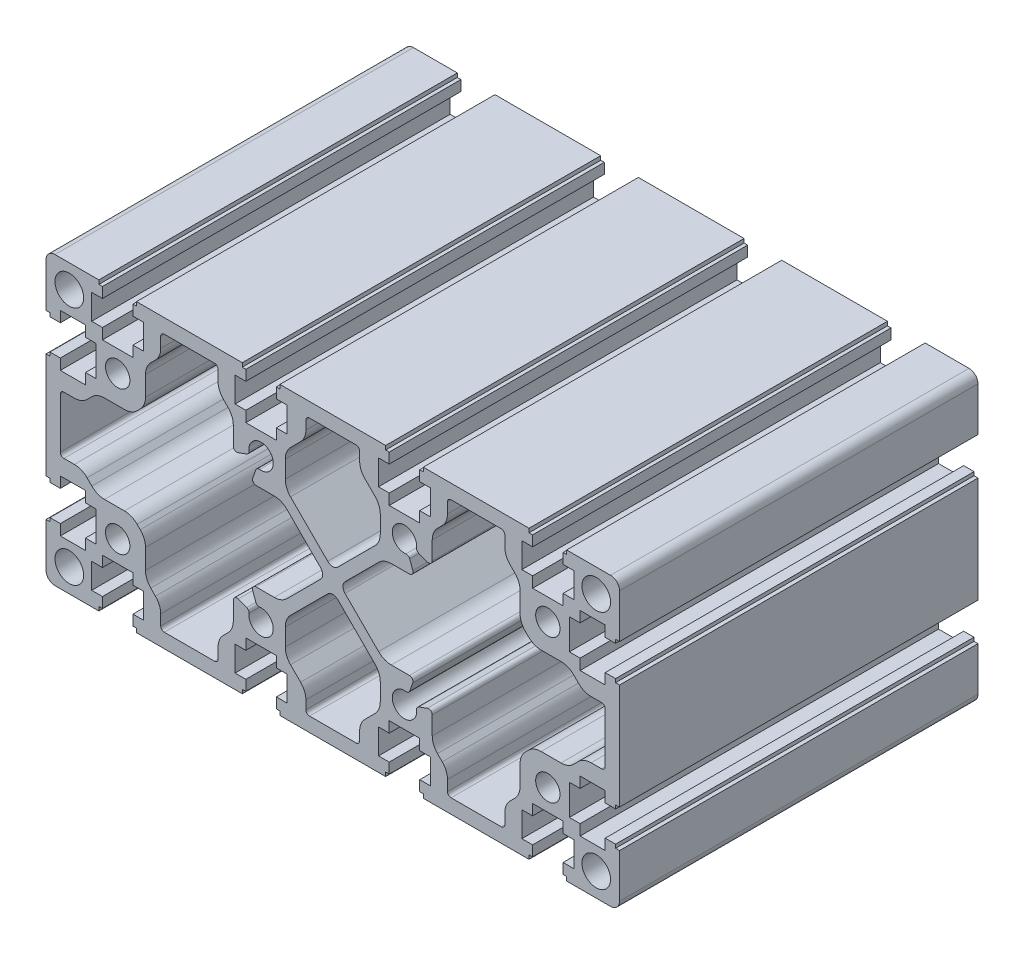
SolidWorks part; units mm, degrees
ref_plane "前视基准面" through (0, 0, 0) normal (0, 0, 1) x (1, 0, 0)
ref_plane "上视基准面" through (0, 0, 0) normal (0, 1, 0) x (1, 0, 0)
ref_plane "右视基准面" through (0, 0, 0) normal (1, 0, 0) x (0, 0, -1)
sketch "草图1" plane through (0, 0, 0) normal (0, 0, 1) x (1, 0, 0)
  line B0 (37.6677, 33.592) -> (38.5345, 35.9736)
  line B1 (35.9736, 38.5345) -> (33.592, 37.6677)
  line B2 (32.25, 38.6074) -> (32.25, 43.6789)
  line B3 (30.7855, 47.2145) -> (29.4645, 48.5355)
  line B4 (28, 52.0711) -> (28, 55)
  line B5 (27, 56) -> (13, 56)
  line B6 (12, 55) -> (12, 52.0711)
  line B7 (10.5355, 48.5355) -> (9.2145, 47.2145)
  line B8 (7.75, 43.6789) -> (7.75, 38.1211)
  line B9 (6.2855, 34.5855) -> (5.4145, 33.7145)
  line B10 (1.8789, 32.25) -> (-3.6789, 32.25)
  line B11 (-7.2145, 30.7855) -> (-8.5355, 29.4645)
  line B12 (-12.0711, 28) -> (-15, 28)
  line B13 (-16, 27) -> (-16, 13)
  line B14 (-15, 12) -> (-12.0711, 12)
  line B15 (-8.5355, 10.5355) -> (-7.2145, 9.2145)
  line B16 (-3.6789, 7.75) -> (1.8789, 7.75)
  line B17 (5.4145, 6.2855) -> (6.2855, 5.4145)
  line B18 (7.75, 1.8789) -> (7.75, -3.6789)
  line B19 (9.2145, -7.2145) -> (10.5355, -8.5355)
  line B20 (12, -12.0711) -> (12, -15)
  line B21 (13, -16) -> (27, -16)
  line B22 (28, -15) -> (28, -12.0711)
  line B23 (29.4645, -8.5355) -> (30.7855, -7.2145)
  line B24 (32.25, -3.6789) -> (32.25, 1.3926)
  line B25 (33.592, 2.3323) -> (35.9736, 1.4655)
  line B26 (38.5345, 4.0264) -> (37.6677, 6.408)
  line B27 (38.6074, 7.75) -> (43.6789, 7.75)
  line B28 (47.2145, 9.2145) -> (56.5858, 18.5858)
  line B29 (56.5858, 21.4142) -> (47.2145, 30.7855)
  line B30 (43.6789, 32.25) -> (38.6074, 32.25)
  line B31 (67.5, -15) -> (67.5, -12.5966)
  line B32 (68.9645, -9.061) -> (71.7855, -6.24)
  line B33 (73.25, -2.7044) -> (73.25, 2.1534)
  line B34 (71.7855, 5.689) -> (61.4142, 16.0603)
  line B35 (58.5858, 16.0603) -> (48.2145, 5.689)
  line B36 (46.75, 2.1534) -> (46.75, -2.7044)
  line B37 (48.2145, -6.24) -> (51.0355, -9.061)
  line B38 (52.5, -12.5966) -> (52.5, -15)
  line B39 (53.5, -16) -> (66.5, -16)
  line B40 (137.5, 60) -> (125.25, 60)
  line B41 (125.25, 60) -> (125.25, 58.9)
  line B42 (125.25, 58.9) -> (124.25, 58.9)
  line B43 (124.25, 58.9) -> (124.25, 56)
  line B44 (124.25, 56) -> (127.25, 56)
  line B45 (127.25, 56) -> (127.25, 49)
  line B46 (127.25, 49) -> (124.25, 49)
  line B47 (124.25, 49) -> (124.25, 46)
  line B48 (124.25, 46) -> (115.75, 46)
  line B49 (115.75, 46) -> (115.75, 49)
  line B50 (115.75, 49) -> (112.75, 49)
  line B51 (112.75, 49) -> (112.75, 56)
  line B52 (112.75, 56) -> (115.75, 56)
  line B53 (115.75, 56) -> (115.75, 58.9)
  line B54 (115.75, 58.9) -> (114.75, 58.9)
  line B55 (114.75, 58.9) -> (114.75, 60)
  line B56 (114.75, 60) -> (85.25, 60)
  line B57 (85.25, 60) -> (85.25, 58.9)
  line B58 (85.25, 58.9) -> (84.25, 58.9)
  line B59 (84.25, 58.9) -> (84.25, 56)
  line B60 (84.25, 56) -> (87.25, 56)
  line B61 (87.25, 56) -> (87.25, 49)
  line B62 (87.25, 49) -> (84.25, 49)
  line B63 (84.25, 49) -> (84.25, 46)
  line B64 (84.25, 46) -> (75.75, 46)
  line B65 (75.75, 46) -> (75.75, 49)
  line B66 (75.75, 49) -> (72.75, 49)
  line B67 (72.75, 49) -> (72.75, 56)
  line B68 (72.75, 56) -> (75.75, 56)
  line B69 (75.75, 56) -> (75.75, 58.9)
  line B70 (75.75, 58.9) -> (74.75, 58.9)
  line B71 (74.75, 58.9) -> (74.75, 60)
  line B72 (74.75, 60) -> (45.25, 60)
  line B73 (45.25, 60) -> (45.25, 58.9)
  line B74 (45.25, 58.9) -> (44.25, 58.9)
  line B75 (44.25, 58.9) -> (44.25, 56)
  line B76 (44.25, 56) -> (47.25, 56)
  line B77 (47.25, 56) -> (47.25, 49)
  line B78 (47.25, 49) -> (44.25, 49)
  line B79 (44.25, 49) -> (44.25, 46)
  line B80 (44.25, 46) -> (35.75, 46)
  line B81 (35.75, 46) -> (35.75, 49)
  line B82 (35.75, 49) -> (32.75, 49)
  line B83 (32.75, 49) -> (32.75, 56)
  line B84 (32.75, 56) -> (35.75, 56)
  line B85 (35.75, 56) -> (35.75, 58.9)
  line B86 (35.75, 58.9) -> (34.75, 58.9)
  line B87 (34.75, 58.9) -> (34.75, 60)
  line B88 (34.75, 60) -> (5.25, 60)
  line B89 (5.25, 60) -> (5.25, 58.9)
  line B90 (5.25, 58.9) -> (4.25, 58.9)
  line B91 (4.25, 58.9) -> (4.25, 56)
  line B92 (4.25, 56) -> (7.25, 56)
  line B93 (7.25, 56) -> (7.25, 49)
  line B94 (7.25, 49) -> (4.25, 49)
  line B95 (4.25, 49) -> (4.25, 46)
  line B96 (4.25, 46) -> (-4.25, 46)
  line B97 (-4.25, 46) -> (-4.25, 49)
  line B98 (-4.25, 49) -> (-7.25, 49)
  line B99 (-7.25, 49) -> (-7.25, 56)
  line B100 (-7.25, 56) -> (-4.25, 56)
  line B101 (-4.25, 56) -> (-4.25, 58.9)
  line B102 (-4.25, 58.9) -> (-5.25, 58.9)
  line B103 (-5.25, 58.9) -> (-5.25, 60)
  line B104 (-5.25, 60) -> (-17.5, 60)
  line B105 (-20, 57.5) -> (-20, 45.25)
  line B106 (-20, 45.25) -> (-18.9, 45.25)
  line B107 (-18.9, 45.25) -> (-18.9, 44.25)
  line B108 (-18.9, 44.25) -> (-16, 44.25)
  line B109 (-16, 44.25) -> (-16, 47.25)
  line B110 (-16, 47.25) -> (-9, 47.25)
  line B111 (-9, 47.25) -> (-9, 44.25)
  line B112 (-9, 44.25) -> (-6, 44.25)
  line B113 (-6, 44.25) -> (-6, 35.75)
  line B114 (-6, 35.75) -> (-9, 35.75)
  line B115 (-9, 35.75) -> (-9, 32.75)
  line B116 (-9, 32.75) -> (-16, 32.75)
  line B117 (-16, 32.75) -> (-16, 35.75)
  line B118 (-16, 35.75) -> (-18.9, 35.75)
  line B119 (-18.9, 35.75) -> (-18.9, 34.75)
  line B120 (-18.9, 34.75) -> (-20, 34.75)
  line B121 (-20, 34.75) -> (-20, 5.25)
  line B122 (-20, 5.25) -> (-18.9, 5.25)
  line B123 (-18.9, 5.25) -> (-18.9, 4.25)
  line B124 (-18.9, 4.25) -> (-16, 4.25)
  line B125 (-16, 4.25) -> (-16, 7.25)
  line B126 (-16, 7.25) -> (-9, 7.25)
  line B127 (-9, 7.25) -> (-9, 4.25)
  line B128 (-9, 4.25) -> (-6, 4.25)
  line B129 (-6, 4.25) -> (-6, -4.25)
  line B130 (-6, -4.25) -> (-9, -4.25)
  line B131 (-9, -4.25) -> (-9, -7.25)
  line B132 (-9, -7.25) -> (-16, -7.25)
  line B133 (-16, -7.25) -> (-16, -4.25)
  line B134 (-16, -4.25) -> (-18.9, -4.25)
  line B135 (-18.9, -4.25) -> (-18.9, -5.25)
  line B136 (-18.9, -5.25) -> (-20, -5.25)
  line B137 (-20, -5.25) -> (-20, -17.5)
  line B138 (-17.5, -20) -> (-5.25, -20)
  line B139 (-5.25, -20) -> (-5.25, -18.9)
  line B140 (-5.25, -18.9) -> (-4.25, -18.9)
  line B141 (-4.25, -18.9) -> (-4.25, -16)
  line B142 (-4.25, -16) -> (-7.25, -16)
  line B143 (-7.25, -16) -> (-7.25, -9)
  line B144 (-7.25, -9) -> (-4.25, -9)
  line B145 (-4.25, -9) -> (-4.25, -6)
  line B146 (-4.25, -6) -> (4.25, -6)
  line B147 (4.25, -6) -> (4.25, -9)
  line B148 (4.25, -9) -> (7.25, -9)
  line B149 (7.25, -9) -> (7.25, -16)
  line B150 (7.25, -16) -> (4.25, -16)
  line B151 (4.25, -16) -> (4.25, -18.9)
  line B152 (4.25, -18.9) -> (5.25, -18.9)
  line B153 (5.25, -18.9) -> (5.25, -20)
  line B154 (5.25, -20) -> (34.75, -20)
  line B155 (34.75, -20) -> (34.75, -18.9)
  line B156 (34.75, -18.9) -> (35.75, -18.9)
  line B157 (35.75, -18.9) -> (35.75, -16)
  line B158 (35.75, -16) -> (32.75, -16)
  line B159 (32.75, -16) -> (32.75, -9)
  line B160 (32.75, -9) -> (35.75, -9)
  line B161 (35.75, -9) -> (35.75, -6)
  line B162 (35.75, -6) -> (44.25, -6)
  line B163 (44.25, -6) -> (44.25, -9)
  line B164 (44.25, -9) -> (47.25, -9)
  line B165 (47.25, -9) -> (47.25, -16)
  line B166 (47.25, -16) -> (44.25, -16)
  line B167 (44.25, -16) -> (44.25, -18.9)
  line B168 (44.25, -18.9) -> (45.25, -18.9)
  line B169 (45.25, -18.9) -> (45.25, -20)
  line B170 (45.25, -20) -> (74.75, -20)
  line B171 (74.75, -20) -> (74.75, -18.9)
  line B172 (74.75, -18.9) -> (75.75, -18.9)
  line B173 (75.75, -18.9) -> (75.75, -16)
  line B174 (75.75, -16) -> (72.75, -16)
  line B175 (72.75, -16) -> (72.75, -9)
  line B176 (72.75, -9) -> (75.75, -9)
  line B177 (75.75, -9) -> (75.75, -6)
  line B178 (75.75, -6) -> (84.25, -6)
  line B179 (84.25, -6) -> (84.25, -9)
  line B180 (84.25, -9) -> (87.25, -9)
  line B181 (87.25, -9) -> (87.25, -16)
  line B182 (87.25, -16) -> (84.25, -16)
  line B183 (84.25, -16) -> (84.25, -18.9)
  line B184 (84.25, -18.9) -> (85.25, -18.9)
  line B185 (85.25, -18.9) -> (85.25, -20)
  line B186 (85.25, -20) -> (114.75, -20)
  line B187 (114.75, -20) -> (114.75, -18.9)
  line B188 (114.75, -18.9) -> (115.75, -18.9)
  line B189 (115.75, -18.9) -> (115.75, -16)
  line B190 (115.75, -16) -> (112.75, -16)
  line B191 (112.75, -16) -> (112.75, -9)
  line B192 (112.75, -9) -> (115.75, -9)
  line B193 (115.75, -9) -> (115.75, -6)
  line B194 (115.75, -6) -> (124.25, -6)
  line B195 (124.25, -6) -> (124.25, -9)
  line B196 (124.25, -9) -> (127.25, -9)
  line B197 (127.25, -9) -> (127.25, -16)
  line B198 (127.25, -16) -> (124.25, -16)
  line B199 (124.25, -16) -> (124.25, -18.9)
  line B200 (124.25, -18.9) -> (125.25, -18.9)
  line B201 (125.25, -18.9) -> (125.25, -20)
  line B202 (125.25, -20) -> (137.5, -20)
  line B203 (140, -17.5) -> (140, -5.25)
  line B204 (140, -5.25) -> (138.9, -5.25)
  line B205 (138.9, -5.25) -> (138.9, -4.25)
  line B206 (138.9, -4.25) -> (136, -4.25)
  line B207 (136, -4.25) -> (136, -7.25)
  line B208 (136, -7.25) -> (129, -7.25)
  line B209 (129, -7.25) -> (129, -4.25)
  line B210 (129, -4.25) -> (126, -4.25)
  line B211 (126, -4.25) -> (126, 4.25)
  line B212 (126, 4.25) -> (129, 4.25)
  line B213 (129, 4.25) -> (129, 7.25)
  line B214 (129, 7.25) -> (136, 7.25)
  line B215 (136, 7.25) -> (136, 4.25)
  line B216 (136, 4.25) -> (138.9, 4.25)
  line B217 (138.9, 4.25) -> (138.9, 5.25)
  line B218 (138.9, 5.25) -> (140, 5.25)
  line B219 (140, 5.25) -> (140, 34.75)
  line B220 (140, 34.75) -> (138.9, 34.75)
  line B221 (138.9, 34.75) -> (138.9, 35.75)
  line B222 (138.9, 35.75) -> (136, 35.75)
  line B223 (136, 35.75) -> (136, 32.75)
  line B224 (136, 32.75) -> (129, 32.75)
  line B225 (129, 32.75) -> (129, 35.75)
  line B226 (129, 35.75) -> (126, 35.75)
  line B227 (126, 35.75) -> (126, 44.25)
  line B228 (126, 44.25) -> (129, 44.25)
  line B229 (129, 44.25) -> (129, 47.25)
  line B230 (129, 47.25) -> (136, 47.25)
  line B231 (136, 47.25) -> (136, 44.25)
  line B232 (136, 44.25) -> (138.9, 44.25)
  line B233 (138.9, 44.25) -> (138.9, 45.25)
  line B234 (138.9, 45.25) -> (140, 45.25)
  line B235 (140, 45.25) -> (140, 57.5)
  line B236 (66.5, 56) -> (53.5, 56)
  line B237 (52.5, 55) -> (52.5, 52.5966)
  line B238 (51.0355, 49.061) -> (48.2145, 46.24)
  line B239 (46.75, 42.7044) -> (46.75, 37.8466)
  line B240 (48.2145, 34.311) -> (58.5858, 23.9397)
  line B241 (61.4142, 23.9397) -> (71.7855, 34.311)
  line B242 (73.25, 37.8466) -> (73.25, 42.7044)
  line B243 (71.7855, 46.24) -> (68.9645, 49.061)
  line B244 (67.5, 52.5966) -> (67.5, 55)
  line B245 (86.408, 37.6677) -> (84.0265, 38.5345)
  line B246 (81.4655, 35.9736) -> (82.3323, 33.592)
  line B247 (81.3926, 32.25) -> (76.3211, 32.25)
  line B248 (72.7855, 30.7855) -> (63.4142, 21.4142)
  line B249 (63.4142, 18.5858) -> (72.7855, 9.2145)
  line B250 (76.3211, 7.75) -> (81.3926, 7.75)
  line B251 (82.3323, 6.408) -> (81.4655, 4.0264)
  line B252 (84.0265, 1.4655) -> (86.408, 2.3323)
  line B253 (87.75, 1.3926) -> (87.75, -3.6789)
  line B254 (89.2145, -7.2145) -> (90.5355, -8.5355)
  line B255 (92, -12.0711) -> (92, -15)
  line B256 (93, -16) -> (107, -16)
  line B257 (108, -15) -> (108, -12.0711)
  line B258 (109.4645, -8.5355) -> (110.7855, -7.2145)
  line B259 (112.25, -3.6789) -> (112.25, 1.8789)
  line B260 (113.7145, 5.4145) -> (114.5855, 6.2855)
  line B261 (118.1211, 7.75) -> (123.6789, 7.75)
  line B262 (127.2145, 9.2145) -> (128.5355, 10.5355)
  line B263 (132.0711, 12) -> (135, 12)
  line B264 (136, 13) -> (136, 27)
  line B265 (135, 28) -> (132.0711, 28)
  line B266 (128.5355, 29.4645) -> (127.2145, 30.7855)
  line B267 (123.6789, 32.25) -> (118.1211, 32.25)
  line B268 (114.5855, 33.7145) -> (113.7145, 34.5855)
  line B269 (112.25, 38.1211) -> (112.25, 43.6789)
  line B270 (110.7855, 47.2145) -> (109.4645, 48.5355)
  line B271 (108, 52.0711) -> (108, 55)
  line B272 (107, 56) -> (93, 56)
  line B273 (92, 55) -> (92, 52.0711)
  line B274 (90.5355, 48.5355) -> (89.2145, 47.2145)
  line B275 (87.75, 43.6789) -> (87.75, 38.6074)
  arc B276 (37.6677, 33.592) -> (38.6074, 32.25) centre (38.6074, 33.25) ccw
  arc B277 (39.5937, 36.6244) -> (38.5345, 35.9736) centre (39.4742, 35.6315) ccw
  arc B278 (39.5937, 36.6244) -> (36.6244, 39.5937) centre (40, 40) ccw
  arc B279 (35.9736, 38.5345) -> (36.6244, 39.5937) centre (35.6315, 39.4742) ccw
  arc B280 (32.25, 38.6074) -> (33.592, 37.6677) centre (33.25, 38.6074) ccw
  arc B281 (32.25, 43.6789) -> (30.7855, 47.2145) centre (27.25, 43.6789) ccw
  arc B282 (28, 52.0711) -> (29.4645, 48.5355) centre (33, 52.0711) ccw
  arc B283 (28, 55) -> (27, 56) centre (27, 55) ccw
  arc B284 (13, 56) -> (12, 55) centre (13, 55) ccw
  arc B285 (10.5355, 48.5355) -> (12, 52.0711) centre (7, 52.0711) ccw
  arc B286 (9.2145, 47.2145) -> (7.75, 43.6789) centre (12.75, 43.6789) ccw
  arc B287 (6.2855, 34.5855) -> (7.75, 38.1211) centre (2.75, 38.1211) ccw
  arc B288 (1.8789, 32.25) -> (5.4145, 33.7145) centre (1.8789, 37.25) ccw
  arc B289 (-3.6789, 32.25) -> (-7.2145, 30.7855) centre (-3.6789, 27.25) ccw
  arc B290 (-12.0711, 28) -> (-8.5355, 29.4645) centre (-12.0711, 33) ccw
  arc B291 (-15, 28) -> (-16, 27) centre (-15, 27) ccw
  arc B292 (-16, 13) -> (-15, 12) centre (-15, 13) ccw
  arc B293 (-8.5355, 10.5355) -> (-12.0711, 12) centre (-12.0711, 7) ccw
  arc B294 (-7.2145, 9.2145) -> (-3.6789, 7.75) centre (-3.6789, 12.75) ccw
  arc B295 (5.4145, 6.2855) -> (1.8789, 7.75) centre (1.8789, 2.75) ccw
  arc B296 (7.75, 1.8789) -> (6.2855, 5.4145) centre (2.75, 1.8789) ccw
  arc B297 (7.75, -3.6789) -> (9.2145, -7.2145) centre (12.75, -3.6789) ccw
  arc B298 (12, -12.0711) -> (10.5355, -8.5355) centre (7, -12.0711) ccw
  arc B299 (12, -15) -> (13, -16) centre (13, -15) ccw
  arc B300 (27, -16) -> (28, -15) centre (27, -15) ccw
  arc B301 (29.4645, -8.5355) -> (28, -12.0711) centre (33, -12.0711) ccw
  arc B302 (30.7855, -7.2145) -> (32.25, -3.6789) centre (27.25, -3.6789) ccw
  arc B303 (33.592, 2.3323) -> (32.25, 1.3926) centre (33.25, 1.3926) ccw
  arc B304 (36.6244, 0.4063) -> (35.9736, 1.4655) centre (35.6315, 0.5258) ccw
  arc B305 (36.6244, 0.4063) -> (39.5937, 3.3756) centre (40, 0) ccw
  arc B306 (38.5345, 4.0264) -> (39.5937, 3.3756) centre (39.4742, 4.3685) ccw
  arc B307 (38.6074, 7.75) -> (37.6677, 6.408) centre (38.6074, 6.75) ccw
  arc B308 (43.6789, 7.75) -> (47.2145, 9.2145) centre (43.6789, 12.75) ccw
  arc B309 (56.5858, 18.5858) -> (56.5858, 21.4142) centre (55.1716, 20) ccw
  arc B310 (47.2145, 30.7855) -> (43.6789, 32.25) centre (43.6789, 27.25) ccw
  arc B311 (66.5, -16) -> (67.5, -15) centre (66.5, -15) ccw
  arc B312 (68.9645, -9.061) -> (67.5, -12.5966) centre (72.5, -12.5966) ccw
  arc B313 (71.7855, -6.24) -> (73.25, -2.7044) centre (68.25, -2.7044) ccw
  arc B314 (73.25, 2.1534) -> (71.7855, 5.689) centre (68.25, 2.1534) ccw
  arc B315 (61.4142, 16.0603) -> (58.5858, 16.0603) centre (60, 14.6461) ccw
  arc B316 (48.2145, 5.689) -> (46.75, 2.1534) centre (51.75, 2.1534) ccw
  arc B317 (46.75, -2.7044) -> (48.2145, -6.24) centre (51.75, -2.7044) ccw
  arc B318 (52.5, -12.5966) -> (51.0355, -9.061) centre (47.5, -12.5966) ccw
  arc B319 (52.5, -15) -> (53.5, -16) centre (53.5, -15) ccw
  arc B320 (140, 57.5) -> (137.5, 60) centre (137.5, 57.5) ccw
  arc B321 (-17.5, 60) -> (-20, 57.5) centre (-17.5, 57.5) ccw
  arc B322 (-20, -17.5) -> (-17.5, -20) centre (-17.5, -17.5) ccw
  arc B323 (137.5, -20) -> (140, -17.5) centre (137.5, -17.5) ccw
  arc B324 (67.5, 55) -> (66.5, 56) centre (66.5, 55) ccw
  arc B325 (53.5, 56) -> (52.5, 55) centre (53.5, 55) ccw
  arc B326 (51.0355, 49.061) -> (52.5, 52.5966) centre (47.5, 52.5966) ccw
  arc B327 (48.2145, 46.24) -> (46.75, 42.7044) centre (51.75, 42.7044) ccw
  arc B328 (46.75, 37.8466) -> (48.2145, 34.311) centre (51.75, 37.8466) ccw
  arc B329 (58.5858, 23.9397) -> (61.4142, 23.9397) centre (60, 25.3539) ccw
  arc B330 (71.7855, 34.311) -> (73.25, 37.8466) centre (68.25, 37.8466) ccw
  arc B331 (73.25, 42.7044) -> (71.7855, 46.24) centre (68.25, 42.7044) ccw
  arc B332 (67.5, 52.5966) -> (68.9645, 49.061) centre (72.5, 52.5966) ccw
  arc B333 (86.408, 37.6677) -> (87.75, 38.6074) centre (86.75, 38.6074) ccw
  arc B334 (83.3756, 39.5937) -> (84.0265, 38.5345) centre (84.3685, 39.4742) ccw
  arc B335 (83.3756, 39.5937) -> (80.4063, 36.6244) centre (80, 40) ccw
  arc B336 (81.4655, 35.9736) -> (80.4063, 36.6244) centre (80.5258, 35.6315) ccw
  arc B337 (81.3926, 32.25) -> (82.3323, 33.592) centre (81.3926, 33.25) ccw
  arc B338 (76.3211, 32.25) -> (72.7855, 30.7855) centre (76.3211, 27.25) ccw
  arc B339 (63.4142, 21.4142) -> (63.4142, 18.5858) centre (64.8284, 20) ccw
  arc B340 (72.7855, 9.2145) -> (76.3211, 7.75) centre (76.3211, 12.75) ccw
  arc B341 (82.3323, 6.408) -> (81.3926, 7.75) centre (81.3926, 6.75) ccw
  arc B342 (80.4063, 3.3756) -> (81.4655, 4.0264) centre (80.5258, 4.3685) ccw
  arc B343 (80.4063, 3.3756) -> (83.3756, 0.4063) centre (80, 0) ccw
  arc B344 (84.0265, 1.4655) -> (83.3756, 0.4063) centre (84.3685, 0.5258) ccw
  arc B345 (87.75, 1.3926) -> (86.408, 2.3323) centre (86.75, 1.3926) ccw
  arc B346 (87.75, -3.6789) -> (89.2145, -7.2145) centre (92.75, -3.6789) ccw
  arc B347 (92, -12.0711) -> (90.5355, -8.5355) centre (87, -12.0711) ccw
  arc B348 (92, -15) -> (93, -16) centre (93, -15) ccw
  arc B349 (107, -16) -> (108, -15) centre (107, -15) ccw
  arc B350 (109.4645, -8.5355) -> (108, -12.0711) centre (113, -12.0711) ccw
  arc B351 (110.7855, -7.2145) -> (112.25, -3.6789) centre (107.25, -3.6789) ccw
  arc B352 (113.7145, 5.4145) -> (112.25, 1.8789) centre (117.25, 1.8789) ccw
  arc B353 (118.1211, 7.75) -> (114.5855, 6.2855) centre (118.1211, 2.75) ccw
  arc B354 (123.6789, 7.75) -> (127.2145, 9.2145) centre (123.6789, 12.75) ccw
  arc B355 (132.0711, 12) -> (128.5355, 10.5355) centre (132.0711, 7) ccw
  arc B356 (135, 12) -> (136, 13) centre (135, 13) ccw
  arc B357 (136, 27) -> (135, 28) centre (135, 27) ccw
  arc B358 (128.5355, 29.4645) -> (132.0711, 28) centre (132.0711, 33) ccw
  arc B359 (127.2145, 30.7855) -> (123.6789, 32.25) centre (123.6789, 27.25) ccw
  arc B360 (114.5855, 33.7145) -> (118.1211, 32.25) centre (118.1211, 37.25) ccw
  arc B361 (112.25, 38.1211) -> (113.7145, 34.5855) centre (117.25, 38.1211) ccw
  arc B362 (112.25, 43.6789) -> (110.7855, 47.2145) centre (107.25, 43.6789) ccw
  arc B363 (108, 52.0711) -> (109.4645, 48.5355) centre (113, 52.0711) ccw
  arc B364 (108, 55) -> (107, 56) centre (107, 55) ccw
  arc B365 (93, 56) -> (92, 55) centre (93, 55) ccw
  arc B366 (90.5355, 48.5355) -> (92, 52.0711) centre (87, 52.0711) ccw
  arc B367 (89.2145, 47.2145) -> (87.75, 43.6789) centre (92.75, 43.6789) ccw
  circle B368 centre (-13.5, -13.5) radius 4
  circle B369 centre (0, 0) radius 3.4
  circle B370 centre (-13.5, 53.5) radius 4
  circle B371 centre (0, 40) radius 3.4
  circle B372 centre (133.5, -13.5) radius 4
  circle B373 centre (120, 0) radius 3.4
  circle B374 centre (133.5, 53.5) radius 4
  circle B375 centre (120, 40) radius 3.4
sketch_block_instance "A$C6E033F3C-1"
sketch_block "A$C6E033F3C"
extrude "凸台-拉伸1" add sketch "草图1" along normal blind 100
